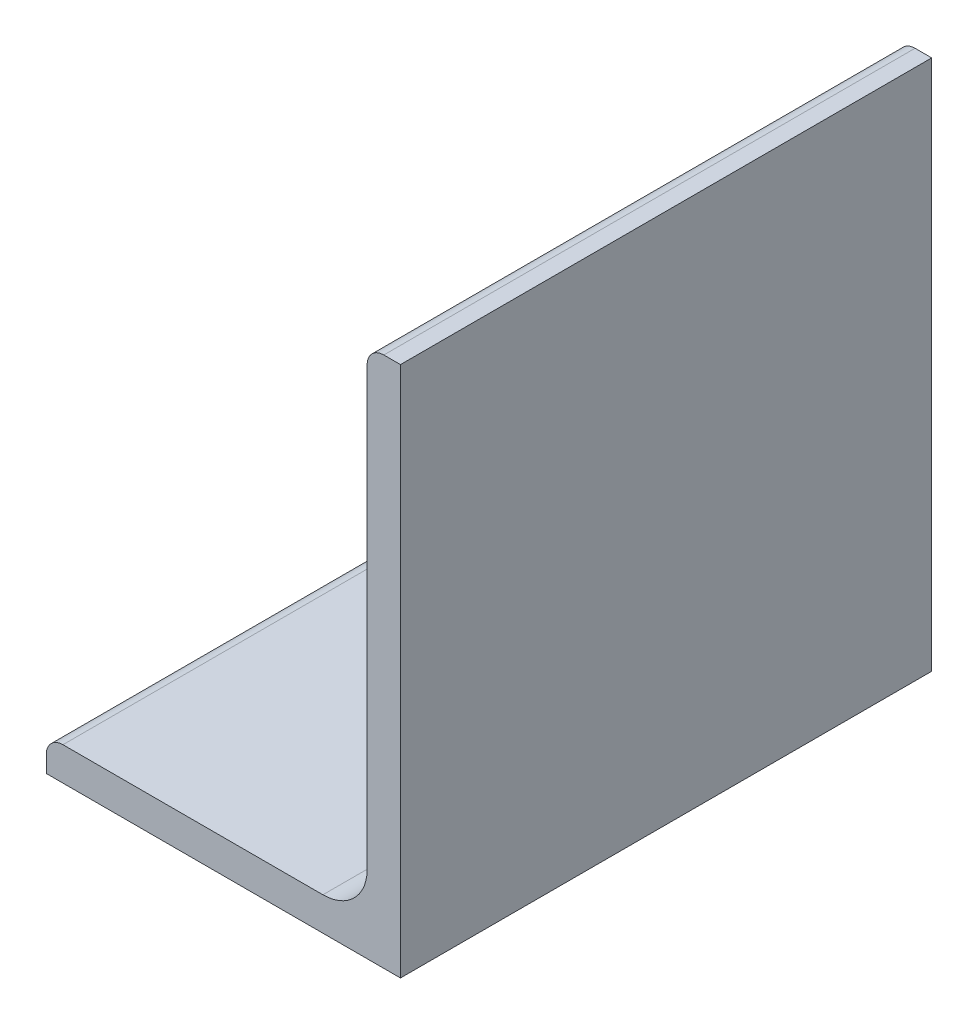
SolidWorks part; units mm, degrees
ref_plane "Front Plane" through (0, 0, 0) normal (0, 0, 1) x (1, 0, 0)
ref_plane "Top Plane" through (0, 0, 0) normal (0, 1, 0) x (1, 0, 0)
ref_plane "Right Plane" through (0, 0, 0) normal (1, 0, 0) x (0, 0, -1)
sketch "Sketch2" plane through (0, 0, 0) normal (0, 0, 1) x (1, 0, 0)
  line L0 (-25.4, 0) -> (25.4, 0)
  line L1 (25.4, 0) -> (25.4, 76.2)
  line L2 (25.4, 76.2) -> (20.6248, 76.2) construction
  line L3 (20.6248, 73.8124) -> (20.6248, 11.1252)
  line L4 (14.2748, 4.7752) -> (-23.0124, 4.7752)
  line L5 (-25.4, 0) -> (-25.4, 4.7752) construction
  line L6 (23.0124, 76.2) -> (25.4, 76.2)
  line L7 (-25.4, 2.3876) -> (-25.4, 0)
  arc A0 (20.6248, 73.8124) -> (23.0124, 76.2) centre (23.0124, 73.8124) cw
  arc A1 (-25.4, 2.3876) -> (-23.0124, 4.7752) centre (-23.0124, 2.3876) cw
  arc A2 (20.6248, 11.1252) -> (14.2748, 4.7752) centre (14.2748, 11.1252) cw
  dimension "Inside Radius" = 6.35
  dimension "Vert" = 76.2
  dimension "Horz" = 50.8
  dimension "Thickness" = 4.7752
extrude "Boss-Extrude1" add sketch "Sketch2" along normal mid plane 76.2
sketch "Break Locations" plane through (0, 0, 0) normal (1, 0, 0) x (0, 0, -1)
  line L1 (-38.1, 0) -> (-38.1, 76.2) construction
  line L2 (38.1, 0) -> (38.1, 76.2) construction
  point P0 (26.67, 0)
  point P1 (-26.67, 0)
  dimension "D1" = 64.77
  dimension "D2" = 64.77
ref_plane "Contact Plane 1" through (0, 4.7752, 0) normal (0, 1, 0) x (1, 0, 0)
ref_plane "Contact Plane 2" through (20.6248, 0, 0) normal (-1, 0, 0) x (0, 0, 1)
equation "\"D1@Break Locations\"=.85*\"Vert@Sketch2\""
equation "\"D2@Break Locations\"=\"D1@Break Locations\""
